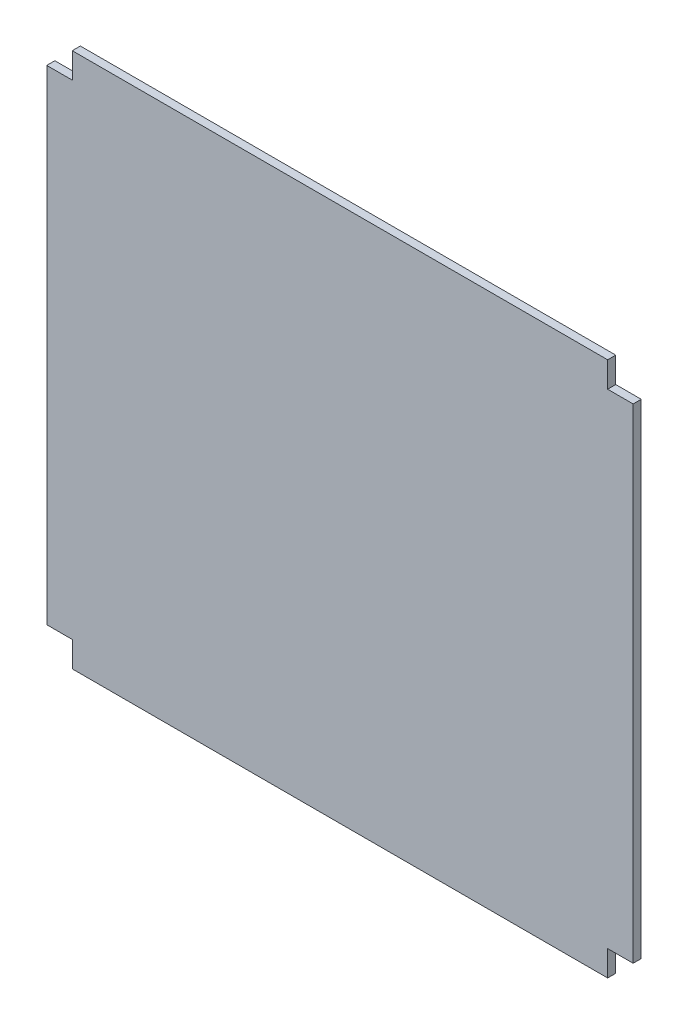
SolidWorks part; units mm, degrees
ref_plane "Alzado" through (0, 0, 0) normal (0, 0, 1) x (1, 0, 0)
ref_plane "Planta" through (0, 0, 0) normal (0, 1, 0) x (1, 0, 0)
ref_plane "Vista lateral" through (0, 0, 0) normal (1, 0, 0) x (0, 0, -1)
sketch "Sketch1" plane through (0, 0, 0) normal (0, 0, 1) x (1, 0, 0)
  line L1 (460, -420) -> (-460, -420)
  line L2 (460, -420) -> (460, 420)
  line L3 (460, 420) -> (-460, 420)
  line L4 (-460, -420) -> (-460, 420)
  line L5 (460, -420) -> (-460, 420) construction
  line L6 (460, 420) -> (-460, -420) construction
  point P0 (0, 0)
  dimension "D1" = 920
  dimension "D2" = 840
extrude "Boss-Extrude1" add sketch "Sketch1" along normal blind 12.7
sketch "Sketch2" plane through (0, 0, 12.7) normal (0, 0, 1) x (1, 0, 0)
  line L1 (-460, 420) -> (-420, 420)
  line L2 (-460, 420) -> (-460, 380)
  line L3 (-460, 380) -> (-420, 380)
  line L4 (-420, 420) -> (-420, 380)
  line L5 (460, -420) -> (420, -420)
  line L6 (460, -420) -> (460, -380)
  line L7 (460, -380) -> (420, -380)
  line L8 (420, -420) -> (420, -380)
  line L9 (460, 420) -> (420, 420)
  line L10 (460, 420) -> (460, 380)
  line L11 (460, 380) -> (420, 380)
  line L12 (420, 420) -> (420, 380)
  line L13 (-460, -420) -> (-420, -420)
  line L14 (-460, -420) -> (-460, -380)
  line L15 (-460, -380) -> (-420, -380)
  line L16 (-420, -420) -> (-420, -380)
  dimension "D1" = 40
extrude "Cut-Extrude1" cut sketch "Sketch2" against normal up to surface (12.7 mm away) up to face at (0, 0, 0)
